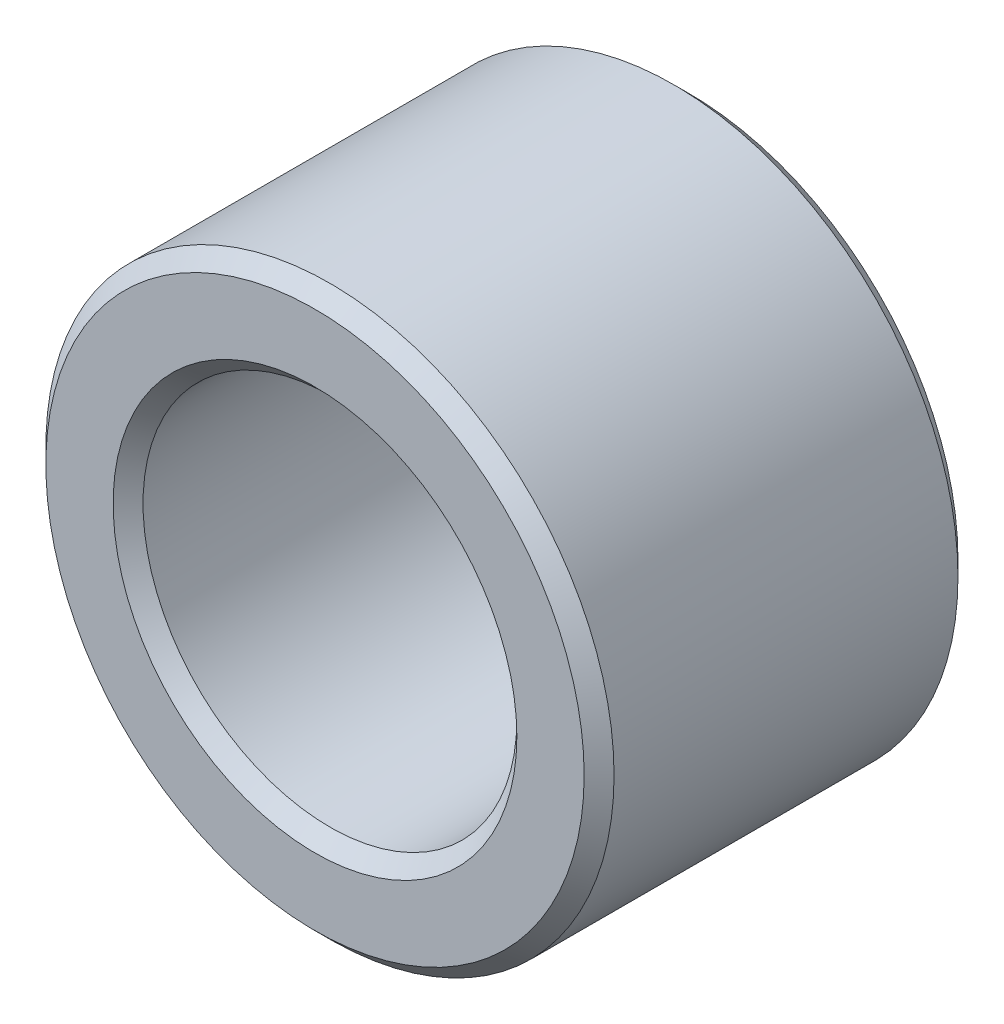
SolidWorks part; units mm, degrees
material "Tin Bearing Bronze"
ref_plane "Front Plane" through (0, 0, 0) normal (0, 0, 1) x (1, 0, 0)
ref_plane "Top Plane" through (0, 0, 0) normal (0, 1, 0) x (1, 0, 0)
ref_plane "Right Plane" through (0, 0, 0) normal (1, 0, 0) x (0, 0, -1)
sketch "Sketch1" plane through (0, 0, 0) normal (0, 0, 1) x (1, 0, 0)
  circle A0 centre (0, 0) radius 4.826
  circle A1 centre (0, 0) radius 3.175
  dimension "D1" = 6.35
  dimension "D2" = 9.652
extrude "Boss-Extrude1" add sketch "Sketch1" along normal blind 6.35
chamfer "Chamfer1" distance 0.254 angle 45 4 edges at (4.826, 0, 0) (3.175, 0, 0) (4.826, 0, 6.35) (3.175, 0, 6.35)
equation "\"ID\" = 0.25"
equation "\"OD\"= 0.375"
equation "\"L\"= 0.25"
